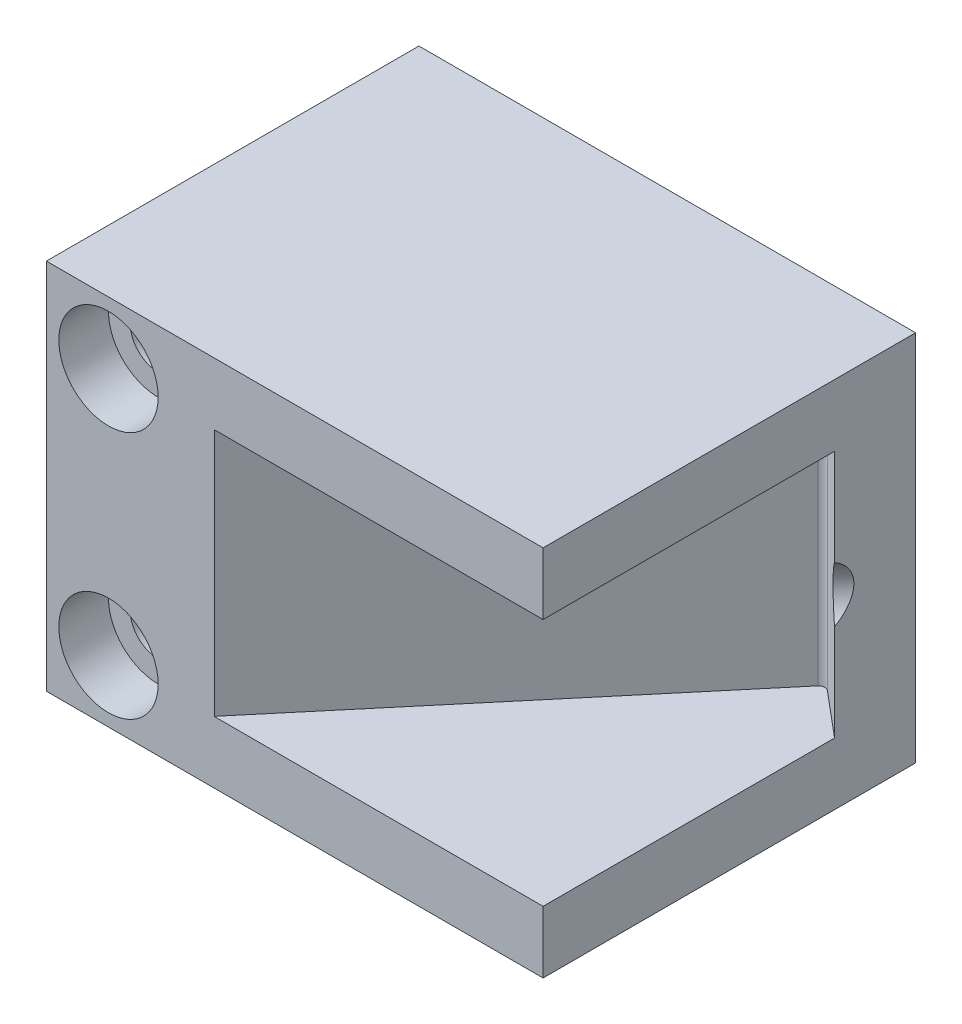
SolidWorks part; units mm, degrees
material "ABS"
ref_plane "前基準面" through (0, 0, 0) normal (0, 0, 1) x (1, 0, 0)
ref_plane "上基準面" through (0, 0, 0) normal (0, 1, 0) x (1, 0, 0)
ref_plane "右基準面" through (0, 0, 0) normal (1, 0, 0) x (0, 0, -1)
sketch "草圖1" plane through (0, 0, 0) normal (0, 0, 1) x (1, 0, 0)
  line L1 (-20, 15) -> (20, 15)
  line L2 (-20, 15) -> (-20, -15)
  line L3 (-20, -15) -> (20, -15)
  line L4 (20, 15) -> (20, -15)
  line L5 (-20, 15) -> (20, -15) construction
  line L6 (-20, -15) -> (20, 15) construction
  point P0 (0, 0)
  dimension "D1" = 40
  dimension "D2" = 30
extrude "填料-伸長1" add sketch "草圖1" along normal mid plane 30
sketch "草圖3" plane through (0, -15, 0) normal (0, -1, 0) x (1, 0, 0)
  line L0 (17, -13) -> (-20, 31.0949)
  line L1 (-20, 15) -> (-20, -15) construction
  line L2 (-20, -15) -> (20, -15) construction
  line L3 (20, 15) -> (20, -15) construction
  dimension "D1" = 50
  dimension "D2" = 2
  dimension "D3" = 3
ref_plane "平面1" through (3.5748, 0, 2.9996) normal (0.766, 0, 0.6428) x (-0.6428, 0, 0.766)
sketch "草圖4" plane through (3.5748, 0, 2.9996) normal (0.766, 0, 0.6428) x (-0.6428, 0, 0.766)
  line L0 (-24.3464, 15) -> (-24.3464, -15) construction
  line L1 (15.6536, -10) -> (-19.3464, -10)
  line L2 (15.6536, -10) -> (15.6536, 10)
  line L3 (15.6536, 10) -> (-19.3464, 10)
  line L4 (-19.3464, -10) -> (-19.3464, 10)
  line L5 (15.6536, -10) -> (-19.3464, 10) construction
  line L6 (15.6536, 10) -> (-19.3464, -10) construction
  point P0 (-1.8464, 0)
  point P9 (-24.3464, 0)
  dimension "D1" = 35
  dimension "D2" = 20
  dimension "D3" = 5
extrude "除料-伸長1" cut sketch "草圖4" along normal through all
fillet "圓角1" radius 0.5 1 edges at (16.0104, 0, -11.8206)
sketch "草圖7" plane through (12.4356, 0, -14.8202) normal (-0.6428, 0, 0.766) x (0.766, 0, 0.6428)
  line L0 (9.8746, -10) -> (9.8746, 10) construction
  line L1 (9.8746, -2.2361) -> (9.8746, 2.2361)
  arc A1 (9.8746, -2.2361) -> (9.8746, 2.2361) centre (11.8746, 0) cw
  point P5 (9.8746, 0)
  dimension "D1" = 2
  dimension "D2" = 3
extrude "除料-伸長4" cut sketch "草圖7" against normal blind 4
hole_wizard "M4 凹頭蓋螺釘的柱孔2" positions "草圖8" profile "草圖9" counterbore size "M4" standard "Ansi Metric" end condition through all
sketch "草圖8" plane through (0, 0, 15) normal (0, 0, 1) x (1, 0, 0)
  line L0 (-20, 0) -> (-6.4763, 0) construction
  line L1 (-20, 15) -> (-20, -15) construction
  line L2 (-6.4763, -10) -> (-6.4763, 10) construction
  line L3 (20, 10) -> (20, 15) construction
  point P0 (-15, 10)
  point P2 (-15, -10)
  dimension "D1" = 20
  dimension "D2" = 35
sketch "草圖9" plane through (-15, 10, 15) normal (1, 0, 0) x (0, -1, 0)
  line L0 (0, 0) -> (0, 30)
  line L1 (0, 30) -> (2.25, 30)
  line L3 (2.25, 30) -> (2.25, 4)
  line L4 (2.25, 4) -> (4, 4)
  line L5 (4, 4) -> (4, 0)
  line L7 (4, 0) -> (0, 0)
  line L11 (0, -6.35) -> (0, 107.95) construction
  dimension "貫穿孔直徑" = 4.5
  dimension "貫穿孔深度" = 30
  dimension "柱孔直徑" = 8
  dimension "柱孔深度" = 4
